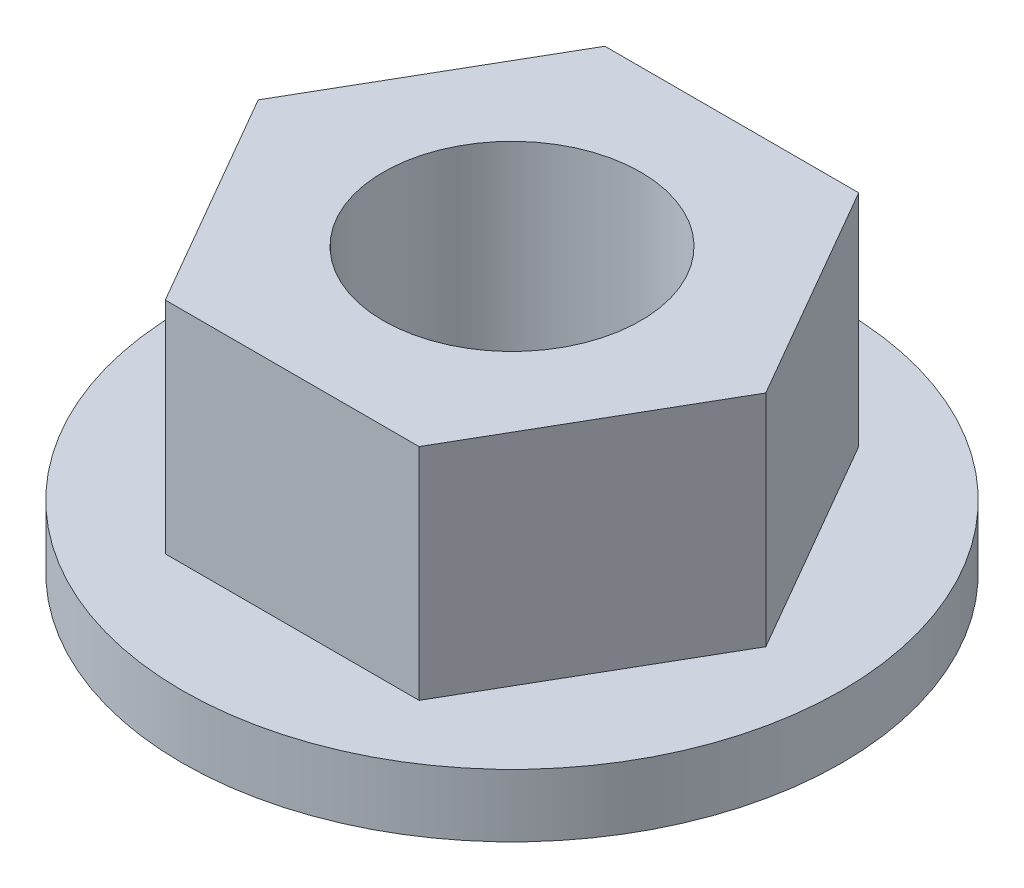
SolidWorks part; units mm, degrees
ref_plane "Front Plane" through (0, 0, 0) normal (0, 0, 1) x (1, 0, 0)
ref_plane "Top Plane" through (0, 0, 0) normal (0, 1, 0) x (1, 0, 0)
ref_plane "Right Plane" through (0, 0, 0) normal (1, 0, 0) x (0, 0, -1)
sketch3d "Hex Nut Sketch datum points"
  point P0 (0, 138.5, 0)
  point P1 (10, 138.5, 0)
  point P2 (0, 138.5, -10)
ref_plane "Hex Nut Sketch plane" through (0, 138.5, 0) normal (0, 1, 0) x (1, 0, 0)
sketch "Hex Nut Sketch" plane through (0, 138.5, 0) normal (0, 1, 0) x (1, 0, 0)
  line L0 (-16.2502, 0) -> (-18.2709, -3.5)
  line L1 (-18.2709, -3.5) -> (-22.3124, -3.5)
  line L2 (-22.3124, -3.5) -> (-24.3331, 0)
  line L3 (-24.3331, 0) -> (-22.3124, 3.5)
  line L4 (-22.3124, 3.5) -> (-18.2709, 3.5)
  line L5 (-18.2709, 3.5) -> (-16.2502, 0)
extrude "Hex Nut" add sketch "Hex Nut Sketch" against normal blind 3.5 separate body
sketch3d "Nut Flange Sketch datum points"
  point P0 (0, 135, 0)
  point P1 (10, 135, 0)
  point P2 (0, 135, -10)
ref_plane "Nut Flange Sketch plane" through (0, 135, 0) normal (0, 1, 0) x (1, 0, 0)
sketch "Nut Flange Sketch" plane through (0, 135, 0) normal (0, 1, 0) x (1, 0, 0)
  circle A0 centre (-20.2917, 0) radius 5.25
extrude "Nut Flange" add sketch "Nut Flange Sketch" against normal blind 1
sketch3d "M4 Internal Thread Blank Sketch datum points"
  point P0 (0, 138.6, 0)
  point P1 (10, 138.6, 0)
  point P2 (0, 138.6, -10)
ref_plane "M4 Internal Thread Blank Sketch plane" through (0, 138.6, 0) normal (0, 1, 0) x (1, 0, 0)
sketch "M4 Internal Thread Blank Sketch" plane through (0, 138.6, 0) normal (0, 1, 0) x (1, 0, 0)
  circle A0 centre (-20.2917, 0) radius 2.05
extrude "M4 Internal Thread Blank" cut sketch "M4 Internal Thread Blank Sketch" against normal blind 4.7
